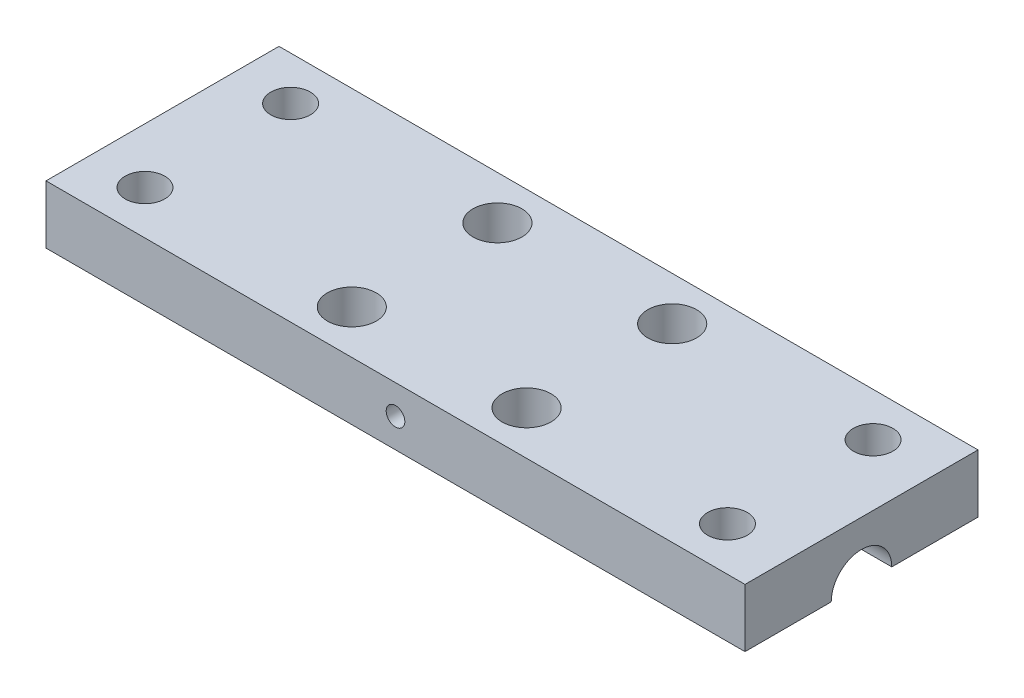
SolidWorks part; units mm, degrees
ref_plane "Front Plane" through (0, 0, 0) normal (0, 0, 1) x (1, 0, 0)
ref_plane "Top Plane" through (0, 0, 0) normal (0, 1, 0) x (1, 0, 0)
ref_plane "Right Plane" through (0, 0, 0) normal (1, 0, 0) x (0, 0, -1)
sketch "Sketch1" plane through (0, 0, 0) normal (0, 1, 0) x (1, 0, 0)
  line L1 (-38.1, 12.7) -> (38.1, 12.7)
  line L2 (-38.1, 12.7) -> (-38.1, -12.7)
  line L3 (-38.1, -12.7) -> (38.1, -12.7)
  line L4 (38.1, 12.7) -> (38.1, -12.7)
  dimension "D1" = 25.4
  dimension "D2" = 76.2
  dimension "D3" = 38.1
  dimension "D4" = 12.7
extrude "Boss-Extrude1" add sketch "Sketch1" along normal blind 6.35
sketch "Sketch2" plane through (0, 6.35, 0) normal (0, 1, 0) x (1, 0, 0)
  circle A0 centre (-32.0741, 7.9375) radius 2.159
  circle A1 centre (-32.0741, -7.9375) radius 2.159
  circle A2 centre (31.4259, 7.9375) radius 2.159
  circle A3 centre (31.4259, -7.9375) radius 2.159
  dimension "D1" = 4.318
  dimension "D2" = 15.875
  dimension "D3" = 63.5
  dimension "D4" = 32.0741
  dimension "D5" = 7.9375
extrude "Cut-Extrude1" cut sketch "Sketch2" against normal through all
sketch "Sketch3" plane through (0, 6.35, 0) normal (0, 1, 0) x (1, 0, 0)
  circle A0 centre (-9.525, 7.9375) radius 2.667
  circle A1 centre (-9.525, -7.9375) radius 2.667
  circle A2 centre (9.525, 7.9375) radius 2.667
  circle A3 centre (9.525, -7.9375) radius 2.667
  dimension "D1" = 5.334
  dimension "D2" = 15.875
  dimension "D3" = 19.05
  dimension "D4" = 7.9375
  dimension "D5" = 9.525
extrude "Cut-Extrude2" cut sketch "Sketch3" against normal through all
sketch "Sketch4" plane through (0, 0, 12.7) normal (0, 0, 1) x (1, 0, 0)
  line L0 (-38.1, 6.35) -> (-38.1, 0) construction
  circle A0 centre (0, 3.175) radius 1.016
  dimension "D1" = 2.032
  dimension "D2" = 3.175
  dimension "D3" = 38.1
extrude "Cut-Extrude3" cut sketch "Sketch4" against normal blind 7.62
sketch "Sketch5" plane through (0, 0, -12.7) normal (0, 0, -1) x (-1, 0, 0)
  line L0 (-38.1, 6.35) -> (-38.1, 0) construction
  circle A0 centre (0, 3.175) radius 1.016
  dimension "D3" = 2.032
  dimension "D1" = 3.175
  dimension "D2" = 38.1
extrude "Cut-Extrude4" cut sketch "Sketch5" against normal blind 7.62
sketch "Sketch7" plane through (38.1, 0, 0) normal (1, 0, 0) x (0, 0, -1)
  circle A0 centre (0, 0) radius 3.302
  dimension "D1" = 6.604
extrude "Cut-Extrude5" cut sketch "Sketch7" against normal through all
